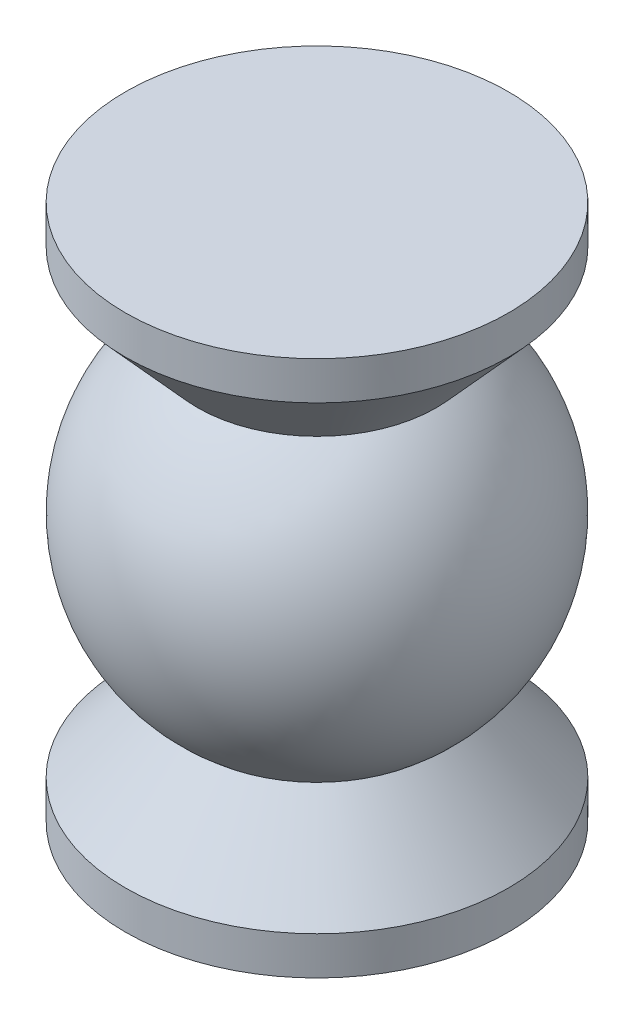
SolidWorks part; units mm, degrees
ref_plane "前视基准面" through (0, 0, 0) normal (0, 0, 1) x (1, 0, 0)
ref_plane "上视基准面" through (0, 0, 0) normal (0, 1, 0) x (1, 0, 0)
ref_plane "右视基准面" through (0, 0, 0) normal (1, 0, 0) x (0, 0, -1)
sketch "草图1" plane through (0, 0, 0) normal (0, 1, 0) x (1, 0, 0)
  circle A0 centre (0, 0) radius 25
extrude "凸台-拉伸1" add sketch "草图1" against normal blind 5
sketch "草图9" plane through (0, 0, 0) normal (0, 0, 1) x (1, 0, 0)
  line L0 (0, 51.1258) -> (0, 1.1258)
  line L1 (15.5728, -15.4427) -> (25, -5)
  line L2 (25, -5) -> (0, -5)
  line L3 (-25, -5) -> (25, -5) construction
  line L4 (0, -5) -> (0, -65)
  line L5 (-15.5728, -15.4427) -> (-27.0739, -15.4427) construction
  line L6 (-25, -5) -> (-25, -35) construction
  line L7 (-25, -35) -> (0, -35) construction
  line L8 (-15.5728, -15.4427) -> (-25, -5)
  line L9 (-15.5728, -54.5573) -> (-25, -65)
  line L10 (15.5728, -54.5573) -> (25, -65)
  line L11 (0, -65) -> (25, -65)
  arc A0 (15.5791, -15.4477) -> (15.5728, -15.4427) centre (0, -35) ccw
  arc A1 (-15.5728, -15.4427) -> (-15.5728, -54.5573) centre (0, -35) ccw
  arc A2 (15.5728, -15.4427) -> (15.5728, -54.5573) centre (0, -35) cw
revolve "旋转20" add sketch "草图9" angle 360 about L0
sketch "草图10" plane through (0, 0, 0) normal (0, 0, 1) x (1, 0, 0)
  line L1 (-4.5989, -35) -> (25, -35) construction
  arc A0 (15.5728, -54.5573) -> (15.5728, -15.4427) centre (0, -35) ccw construction
ref_plane "基准面1" through (0, -35, 0) normal (0, 1, 0) x (1, 0, 0)
mirror "镜向1" about plane through (0, -35, 0) normal (0, 1, 0) of "凸台-拉伸1"
